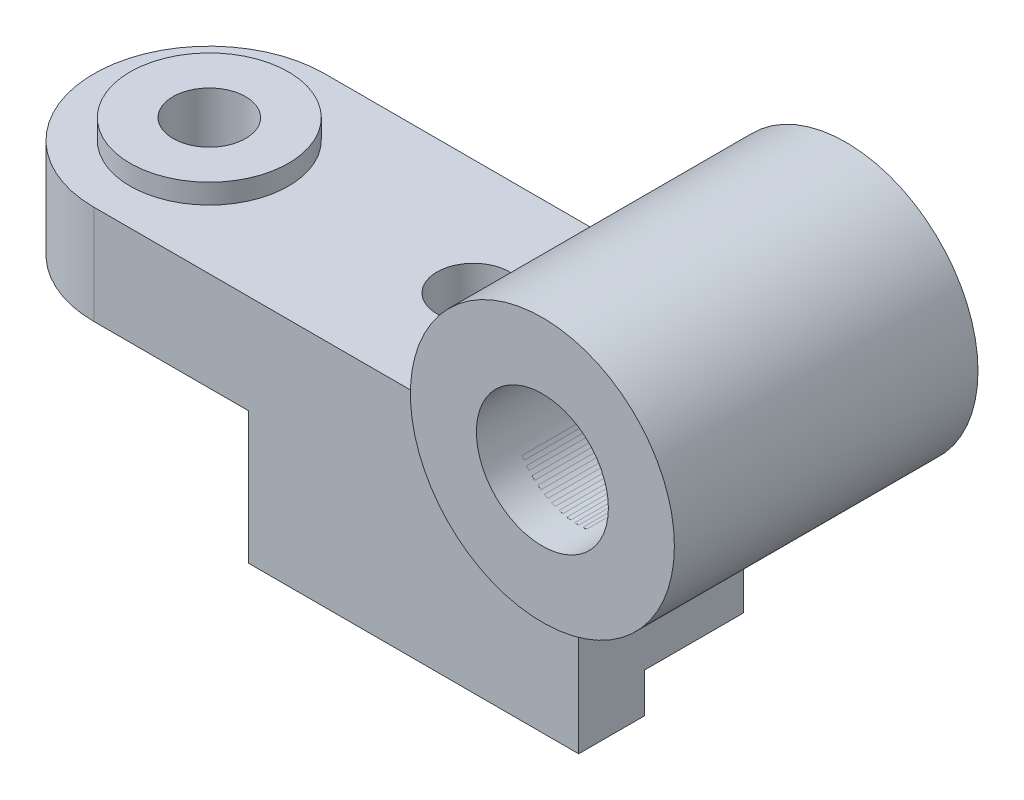
SolidWorks part; units mm, degrees
ref_plane "Ön Düzlem" through (0, 0, 0) normal (0, 0, 1) x (1, 0, 0)
ref_plane "Üst Düzlem" through (0, 0, 0) normal (0, 1, 0) x (1, 0, 0)
ref_plane "Sağ Düzlem" through (0, 0, 0) normal (1, 0, 0) x (0, 0, -1)
sketch "Çizim2" plane through (0, 0, 0) normal (0, 0, 1) x (1, 0, 0)
  line L0 (0, -20) -> (0, -40)
  line L1 (0, -40) -> (-50, -40)
  line L2 (0, -20) -> (-50, -20)
  line L3 (-50, -20) -> (-50, -40)
  circle A0 centre (0, 0) radius 20
  circle A1 centre (0, 0) radius 10
  dimension "D1" = 20
  dimension "D2" = 40
  dimension "D3" = 50
  dimension "D4" = 40
extrude "Yükseklik-Ekstrüzyon1" add sketch "Çizim2" against normal blind 10 contours L2 L3 L1 L0
sketch "Çizim5" plane through (0, 0, -10) normal (0, 0, -1) x (-1, 0, 0)
  line L0 (50, -20) -> (50, -40) construction
  line L1 (0, -20) -> (50, -20)
  line L2 (0, -20) -> (0, -34)
  line L3 (0, -34) -> (50, -34)
  line L4 (50, -20) -> (50, -34)
  dimension "D1" = 6
extrude "Yükseklik-Ekstrüzyon2" add sketch "Çizim5" along normal blind 15
ref_plane "Düzlem1" through (0, 0, 5.5) normal (0, 0, 1) x (1, 0, 0)
sketch "Çizim9" plane through (0, 0, 5.5) normal (0, 0, 1) x (1, 0, 0)
  circle A0 centre (0, 0) radius 20
  circle A1 centre (0, 0) radius 10
  dimension "D1" = 20
extrude "Yükseklik-Ekstrüzyon3" add sketch "Çizim9" against normal blind 46 separate body
ref_plane "Düzlem8" through (0, -5, 0) normal (0, 1, 0) x (1, 0, 0)
sketch "Çizim7" plane through (0, -5, 0) normal (0, 1, 0) x (1, 0, 0)
  line L0 (-66.4591, 17.5) -> (28.5635, 17.5) construction
  line L2 (-73.466, 0) -> (-20, 0)
  line L3 (-20, 40.5) -> (-20, -5.5) construction
  line L4 (0, 0) -> (-50, 0) construction
  line L6 (-20, 35) -> (-73.466, 35)
  line L7 (-20, 35) -> (-15.9537, 35)
  line L9 (-15.9537, 0) -> (-20, 0)
  line L10 (-15.9537, 0) -> (1.534, 0)
  line L11 (-15.9537, 35) -> (1.534, 35)
  line L12 (1.534, 35) -> (1.534, 0)
  arc A0 (-73.466, 35) -> (-73.466, 0) centre (-73.466, 17.5) ccw
  point P1 (1.534, 17.5)
  dimension "D1" = 75
extrude "Yükseklik-Ekstrüzyon4" add sketch "Çizim7" against normal blind 15
sketch "Çizim10" plane through (0, 0, 5.5) normal (0, 0, 1) x (1, 0, 0)
  circle A0 centre (0, 0) radius 10
  dimension "D1" = 20
extrude "Kes-Ekstrüzyon1" cut sketch "Çizim10" against normal blind 62
sketch "Çizim11" plane through (0, -5, 0) normal (0, 1, 0) x (1, 0, 0)
  circle A0 centre (-73.466, 17.5) radius 12
  dimension "D1" = 24
extrude "Yükseklik-Ekstrüzyon5" add sketch "Çizim11" along normal blind 3
sketch "Çizim12" plane through (0, -2, 0) normal (0, 1, 0) x (1, 0, 0)
  circle A0 centre (-73.466, 17.5) radius 5.5
  dimension "D1" = 11
extrude "Kes-Ekstrüzyon2" cut sketch "Çizim12" against normal blind 33
sketch "Çizim13" plane through (0, -5, 0) normal (0, 1, 0) x (1, 0, 0)
  line L0 (-60.6181, 17.5) -> (-102.2586, 17.5) construction
  circle A0 centre (-33.466, 17.5) radius 5.5
  point P6 (-73.466, 17.5)
  dimension "D1" = 11
  dimension "D2" = 40
extrude "Kes-Ekstrüzyon3" cut sketch "Çizim13" against normal blind 33 contours A0
